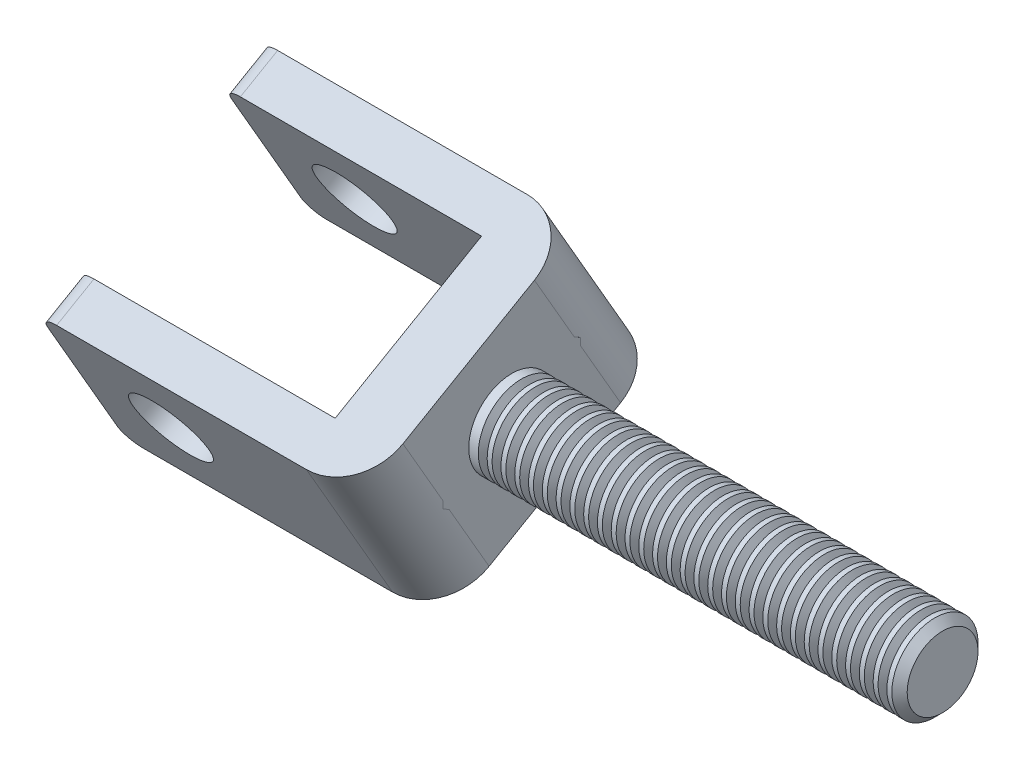
SolidWorks part; units mm, degrees
ref_plane "Front Plane" through (0, 0, 0) normal (0, 0, 1) x (1, 0, 0)
ref_plane "Top Plane" through (0, 0, 0) normal (0, 1, 0) x (1, 0, 0)
ref_plane "Right Plane" through (0, 0, 0) normal (1, 0, 0) x (0, 0, -1)
other "Configuration Table"
sketch "BaseHeadSke" plane through (0, 0, 0) normal (1, 0, 0) x (0, 0, -1)
  line L1 (0, 4.6188) -> (-4, 2.3094)
  line L2 (-4, 2.3094) -> (-4, -2.3094)
  line L3 (-4, -2.3094) -> (0, -4.6188)
  line L4 (0, -4.6188) -> (4, -2.3094)
  line L5 (4, -2.3094) -> (4, 2.3094)
  line L6 (4, 2.3094) -> (0, 4.6188)
  circle A0 centre (0, 0) radius 4 construction
  dimension "Width_flats" = 8
extrude "BaseHead" add sketch "BaseHeadSke" along normal blind 3.5
sketch "HeadChamferSke" plane through (0, 0, 0) normal (0, 0, 1) x (1, 0, 0)
  line L0 (0, 0) -> (108.1848, 0) construction
  line L1 (0, 2.3094) -> (0, -2.3094) construction
  line L2 (0, 4.6188) -> (0, 4)
  line L3 (0, 4) -> (0.3573, 4.6188)
  line L4 (0.3573, 4.6188) -> (0, 4.6188)
  line L7 (3.5, 4.6188) -> (0, 4.6188) construction
  dimension "Angle_Chamfer_Head" = 30
revolve "HeadChamfer" cut sketch "HeadChamferSke" angle 360 about L0
sketch "BodySke" plane through (0, 0, 0) normal (0, 0, 1) x (1, 0, 0)
  line L0 (0, 0) -> (440.8544, 0) construction
  line L1 (0, 0) -> (0, 2.5)
  line L3 (0, 3.4641) -> (0, 0) construction
  line L4 (0, 2.5) -> (28.055, 2.5)
  line L5 (28.055, 2.5) -> (28.5, 2.055)
  line L6 (28.5, 2.055) -> (28.5, 0)
  line L7 (28.5, 0) -> (0, 0)
  line L8 (4.3, 0) -> (4.3, 20.794) construction
  line L9 (3.5, 2.3094) -> (3.5, -2.3094) construction
  line L10 (3.5, 0) -> (3.5, 20.794) construction
  dimension "Thread_minor" = 4.11
  dimension "Advance" = 0.8
  dimension "Length" = 25
  dimension "Diameter" = 5
  dimension "Body_Chamfer_Angle" = 45
  dimension "Thread_length" = 25
revolve "BaseBody" add sketch "BodySke" angle 360 about L0
cosmetic thread "ThreadCosmetic" [suppressed] parameters "Thread_minor"=4.11
sketch "BearingFaceSke" plane through (0, 0, 0) normal (0, 0, 1) x (1, 0, 0)
  line L0 (0, 0) -> (414.2241, 0) construction
  line L1 (3.5, 4.6188) -> (3.5, 2.3094) construction
  line L2 (3.5, 4) -> (3, 4)
  line L3 (3.5, 4) -> (3.5, 14)
  line L4 (3.5, 14) -> (3, 14)
  line L5 (3, 4) -> (3, 14)
  dimension "D1" = 10
  dimension "D2" = 8
  dimension "Bearing_height" = 0.5
revolve "BearingFace" [suppressed] cut sketch "BearingFaceSke" angle 360 about L0
fillet "HeadFillet" [suppressed] radius 0.2
sketch "ThdSchSke" plane through (0, 0, 0) normal (0, 0, 1) x (1, 0, 0)
  line L0 (0, 0) -> (453.2163, 0) construction
  line L1 (27.255, 3.0138) -> (27.255, 2.5)
  line L2 (27.255, 3.0138) -> (27.7688, 3.0138)
  line L3 (27.7688, 3.0138) -> (27.7688, 2.5)
  line L4 (27.7688, 2.5) -> (27.5119, 2.055)
  line L5 (27.5119, 2.055) -> (27.255, 2.5)
  dimension "D1" = 0.8
revolve "ThreadSchematic" cut sketch "ThdSchSke" angle 360 about L0
pattern_linear "ThdSchPat" count 30 spacing 0.8 along (-1, 0, 0) of "ThreadSchematic"
ref_plane "Plane1" through (0, 0, 0) normal (0, -0.866, -0.5) x (-1, 0, 0)
sketch "Sketch1" plane through (0, 0, 0) normal (0, -0.866, -0.5) x (-1, 0, 0)
  line L0 (0, 7.401) -> (15, 7.401)
  line L1 (15, 7.401) -> (15, 4.901)
  line L2 (15, 4.901) -> (0, 4.901)
  line L3 (0, 4.901) -> (0, 0)
  line L4 (0, 0) -> (0, -4.9095)
  line L5 (0, -4.9095) -> (15, -4.9095)
  line L6 (15, -4.9095) -> (15, -7.4095)
  line L7 (15, -7.4095) -> (-0.5, -7.4095)
  line L8 (-3.5, -4.4095) -> (-3.5, 4.401)
  line L9 (-0.5, 7.401) -> (0, 7.401)
  arc A0 (-0.5, -7.4095) -> (-3.5, -4.4095) centre (-0.5, -4.4095) cw
  arc A1 (-3.5, 4.401) -> (-0.5, 7.401) centre (-0.5, 4.401) cw
  dimension "D3" = 3
  dimension "D1" = 2.5
  dimension "D2" = 2.5
  dimension "D4" = 15
  dimension "D5" = 15
extrude "Boss-Extrude1" add sketch "Sketch1" along normal mid plane 10
fillet "Fillet1" radius 1 4 edges at (-15, -1.2546, -7.8269) (-15, -7.4099, 2.8343) (-15, 7.4056, -2.8269) (-15, 1.2504, 7.8343)
sketch "Sketch2" plane through (0, -3.7048, 6.4169) normal (0, -0.5, 0.866) x (1, 0, 0)
  circle A0 centre (-9.8676, 0) radius 2.2104
  point P2 (-3.4208, 0)
  point P3 (-9.8676, 0)
extrude "Cut-Extrude1" cut sketch "Sketch2" against normal blind 23
equation "\"Thread_minor@ThreadCosmetic\" = \"Thread_minor@BodySke\""
equation "\"D2@BearingFaceSke\" = \"Width_flats@BaseHeadSke\""
equation "\"D1@ThdSchSke\" = \"Advance@BodySke\""
equation "\"Advance@ThdSchPat\" = \"Advance@BodySke\""
equation "\"Tooth_Num@ThdSchPat\" =  int( \"Thread_length@BodySke\" / \"Advance@BodySke\" ) - 1 "
